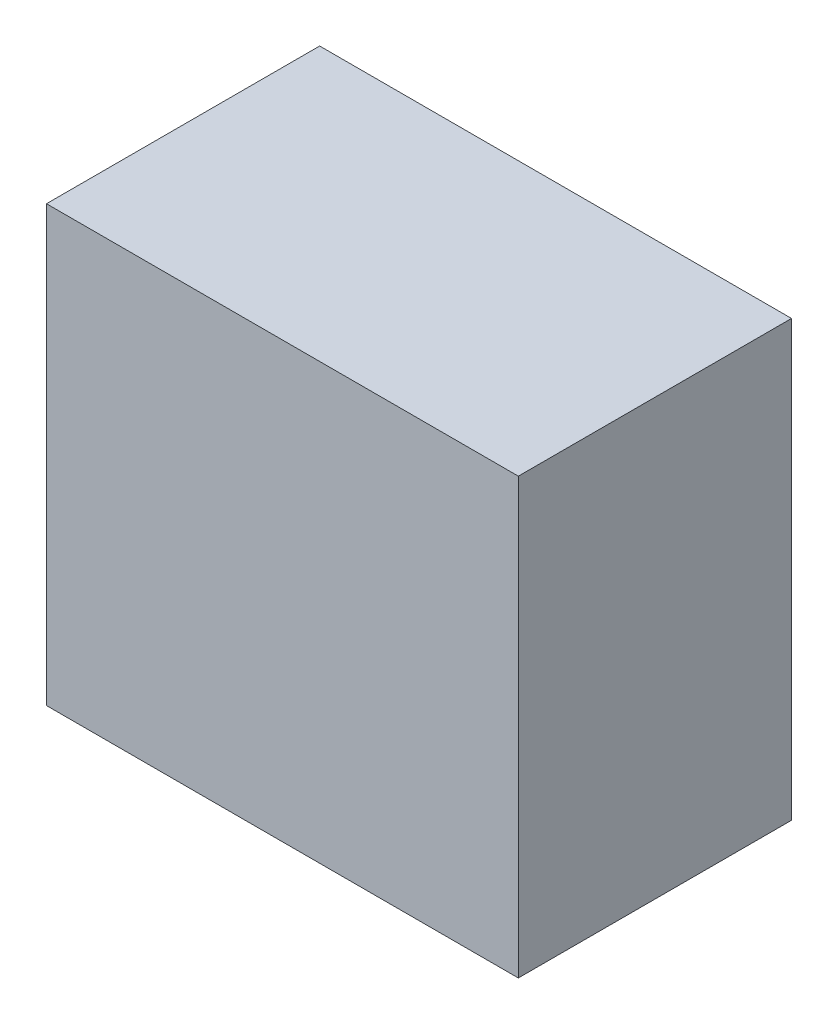
SolidWorks part; units mm, degrees
ref_plane "前视基准面" through (0, 0, 0) normal (0, 0, 1) x (1, 0, 0)
ref_plane "上视基准面" through (0, 0, 0) normal (0, 1, 0) x (1, 0, 0)
ref_plane "右视基准面" through (0, 0, 0) normal (1, 0, 0) x (0, 0, -1)
other "Configuration Table"
sketch "草图1" plane through (0, 0, 0) normal (0, 0, 1) x (1, 0, 0)
  line L1 (-19, -17.5) -> (19, -17.5)
  line L2 (-19, -17.5) -> (-19, 17.5)
  line L3 (-19, 17.5) -> (19, 17.5)
  line L4 (19, -17.5) -> (19, 17.5)
  line L5 (-19, -17.5) -> (19, 17.5) construction
  line L6 (-19, 17.5) -> (19, -17.5) construction
  point P0 (0, 0)
extrude "凸台-拉伸1" add sketch "草图1" along normal blind 22
